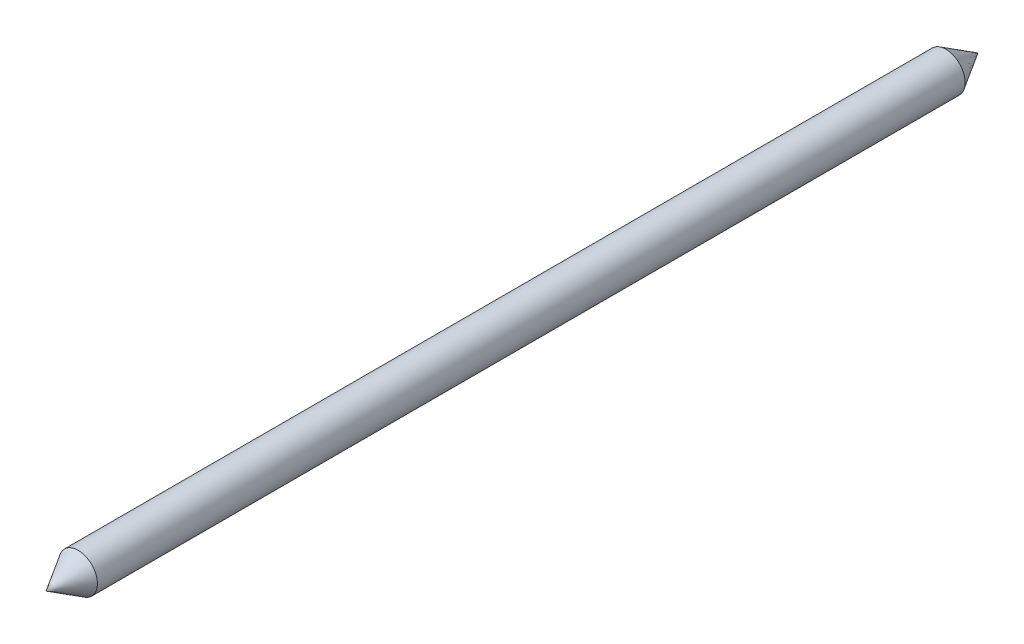
SolidWorks part; units mm, degrees
ref_plane "Front Plane" through (0, 0, 0) normal (0, 0, 1) x (1, 0, 0)
ref_plane "Top Plane" through (0, 0, 0) normal (0, 1, 0) x (1, 0, 0)
ref_plane "Right Plane" through (0, 0, 0) normal (1, 0, 0) x (0, 0, -1)
sketch "Sketch1" plane through (0, 0, 0) normal (0, 1, 0) x (1, 0, 0)
  line L0 (0, 184.15) -> (0, -184.15)
  line L1 (0, -184.15) -> (7.62, -171.45)
  line L2 (7.62, -171.45) -> (7.62, 171.45)
  line L3 (7.62, 171.45) -> (0, 184.15)
  point P2 (0, 0)
  point P5 (7.62, 0)
  dimension "D1" = 368.3
  dimension "D2" = 7.62
  dimension "D3" = 12.7
revolve "Revolve1" add sketch "Sketch1" angle 360 about L0
